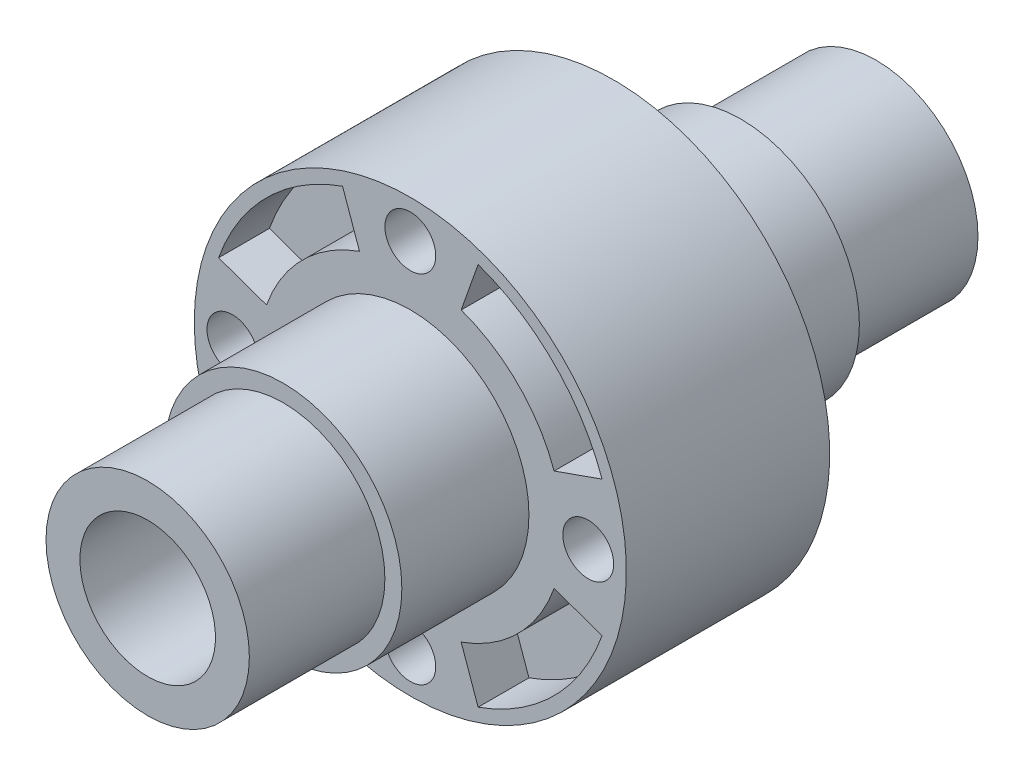
SolidWorks part; units mm, degrees
ref_plane "前视基准面" through (0, 0, 0) normal (0, 0, 1) x (1, 0, 0)
ref_plane "上视基准面" through (0, 0, 0) normal (0, 1, 0) x (1, 0, 0)
ref_plane "右视基准面" through (0, 0, 0) normal (1, 0, 0) x (0, 0, -1)
sketch "草图1" plane through (0, 0, 0) normal (1, 0, 0) x (0, 0, -1)
  line L0 (-21.2214, 0) -> (28.1258, 0) construction
  line L1 (-21.5, 0) -> (-21.5, 6)
  line L2 (-21.5, 6) -> (-13.5, 6)
  line L3 (-13.5, 6) -> (-13.5, 7)
  line L4 (-13.5, 7) -> (-6, 7)
  line L5 (-6, 7) -> (-6, 14)
  line L6 (-6, 14) -> (6, 14)
  line L7 (0, 14) -> (0, 0) construction
  line L8 (6, 7) -> (6, 14)
  line L9 (13.5, 7) -> (6, 7)
  line L10 (13.5, 6) -> (13.5, 7)
  line L11 (21.5, 6) -> (13.5, 6)
  line L12 (21.5, 0) -> (21.5, 6)
  line L13 (-21.5, 0) -> (21.5, 0)
  dimension "D1" = 6
  dimension "D2" = 12
  dimension "D3" = 14
  dimension "D4" = 8
  dimension "D5" = 7.5
  dimension "D6" = 7
revolve "旋转1" add sketch "草图1" angle 360 about L13
sketch "草图2" plane through (0, 0, 6) normal (0, 0, 1) x (1, 0, 0)
  line L0 (0, 0) -> (0, 10.5) construction
  circle A0 centre (0, 0) radius 10.5 construction
  circle A1 centre (0, 10.5) radius 1.5
  circle A2 centre (0, 0) radius 10.5 construction
  circle A3 centre (10.5, 0) radius 1.5
  circle A4 centre (0, 0) radius 10.5 construction
  circle A5 centre (0, -10.5) radius 1.5
  circle A6 centre (0, 0) radius 10.5 construction
  circle A7 centre (-10.5, 0) radius 1.5
  dimension "D1" = 21
  dimension "D2" = 3
  dimension "D3" = 4
extrude "切除-拉伸1" cut sketch "草图2" against normal through all
sketch "草图4" plane through (0, 0, -6) normal (0, 0, -1) x (-1, 0, 0)
  circle A0 centre (0, 0) radius 12.75
  circle A1 centre (0, 0) radius 14 construction
  circle A2 centre (0, 0) radius 14
  dimension "D1" = 25.5
extrude "切除-拉伸4" cut sketch "草图4" against normal through all
sketch "草图5" plane through (0, 0, -6) normal (0, 0, -1) x (-1, 0, 0)
  line L0 (-11.3137, 4) -> (-8.4853, 3)
  line L1 (-4, 11.3137) -> (-3, 8.4853)
  line L2 (4, 11.3137) -> (3, 8.4853)
  line L3 (11.3137, 4) -> (8.4853, 3)
  line L4 (11.3137, -4) -> (8.4853, -3)
  line L5 (4, -11.3137) -> (3, -8.4853)
  line L6 (-4, -11.3137) -> (-3, -8.4853)
  line L7 (-11.3137, -4) -> (-8.4853, -3)
  circle A2 centre (-10.5, 0) radius 1.5 construction
  circle A4 centre (0, 10.5) radius 1.5 construction
  arc A6 (-3, 8.4853) -> (-8.4853, 3) centre (0, 0) ccw
  arc A7 (-4, 11.3137) -> (-11.3137, 4) centre (0, 0) ccw
  arc A8 (8.4853, 3) -> (3, 8.4853) centre (0, 0) ccw
  arc A9 (11.3137, 4) -> (4, 11.3137) centre (0, 0) ccw
  arc A10 (3, -8.4853) -> (8.4853, -3) centre (0, 0) ccw
  arc A11 (4, -11.3137) -> (11.3137, -4) centre (0, 0) ccw
  arc A12 (-8.4853, -3) -> (-3, -8.4853) centre (0, 0) ccw
  arc A13 (-11.3137, -4) -> (-4, -11.3137) centre (0, 0) ccw
  point P25 (0, 0)
  dimension "D3" = 12
  dimension "D4" = 9
  dimension "D1" = 4
  dimension "D2" = 4
  dimension "D5" = 4
extrude "切除-拉伸5" cut sketch "草图5" against normal blind 3
mirror "镜向2" about plane through (0, 0, 0) normal (0, 0, 1) of "切除-拉伸5"
sketch "草图6" plane through (0, 0, -21.5) normal (0, 0, -1) x (-1, 0, 0)
  circle A0 centre (0, 0) radius 4
  dimension "D1" = 8
extrude "切除-拉伸6" cut sketch "草图6" against normal through all
